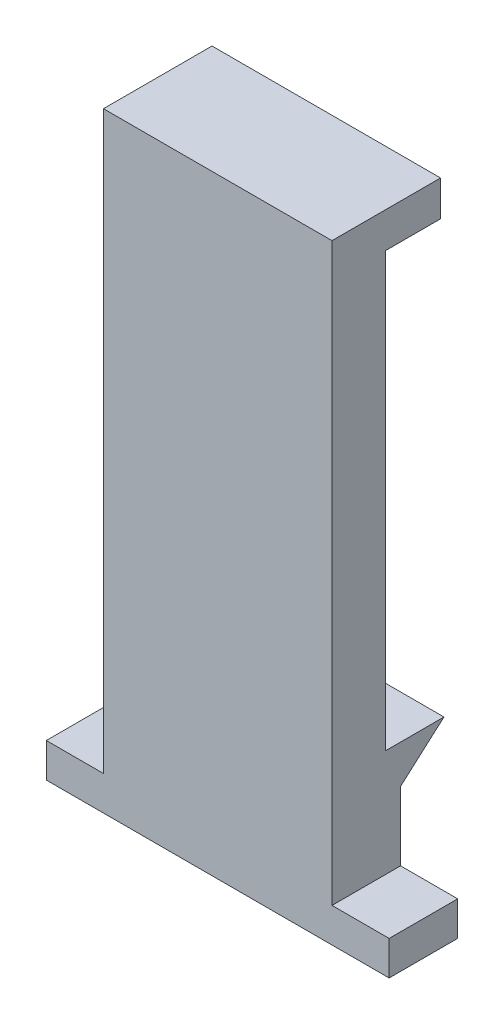
SolidWorks part; units mm, degrees
ref_plane "Front Plane" through (0, 0, 0) normal (0, 0, 1) x (1, 0, 0)
ref_plane "Top Plane" through (0, 0, 0) normal (0, 1, 0) x (1, 0, 0)
ref_plane "Right Plane" through (0, 0, 0) normal (1, 0, 0) x (0, 0, -1)
sketch "Sketch1" plane through (0, 0, 0) normal (1, 0, 0) x (0, 0, -1)
  line L0 (-9.8, -12.38) -> (-3.8, -12.38)
  line L1 (-3.8, -12.38) -> (-3.8, -3.3571)
  line L2 (-3.8, -3.3571) -> (0, 0)
  line L3 (0, 0) -> (-5.1, 0)
  line L4 (-5.1, 0) -> (-5.1, 37.9)
  line L5 (-5.1, 37.9) -> (-0.3, 37.9)
  line L6 (-0.3, 37.9) -> (-0.3, 41)
  line L7 (-0.3, 41) -> (-9.8, 41)
  line L8 (-9.8, 41) -> (-9.8, -12.38)
  point P2 (0, 0)
  point P10 (0, 0)
  point P11 (-11.1386, 0)
  point P12 (-6.0914, -3.6161)
  dimension "D1" = 6
  dimension "D2" = 9.5
  dimension "D3" = 37.9
  dimension "D4" = 41
  dimension "D5" = 4.7
  dimension "D6" = 9.8
  dimension "D7" = 12.38
  dimension "D8" = 3.6
extrude "Boss-Extrude1" add sketch "Sketch1" along normal blind 20 contours L8 L0 L1 L2 L3 L4 L5 L6 L7
sketch "Sketch2" plane through (0, -12.38, 0) normal (0, -1, 0) x (1, 0, 0)
  line L0 (20, 0) -> (0, 0) construction
  line L1 (-5, 9.8) -> (25, 9.8)
  line L2 (-5, 9.8) -> (-5, 3.8)
  line L3 (-5, 3.8) -> (25, 3.8)
  line L4 (25, 9.8) -> (25, 3.8)
  line L5 (20, 9.8) -> (0, 9.8) construction
  line L6 (20, 3.8) -> (0, 3.8) construction
  point P6 (10, 0)
  point P7 (10, 9.8)
  point P8 (-5, 10.4233)
  dimension "D1" = 30
extrude "Boss-Extrude2" add sketch "Sketch2" against normal blind 3 contours L2 L1 L4 L3
